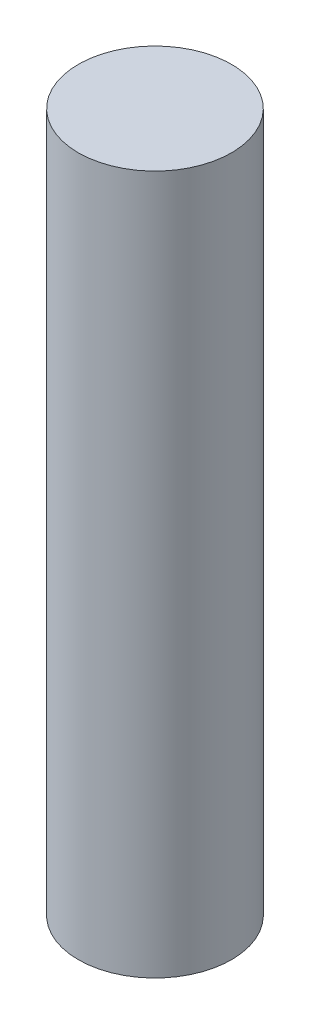
SolidWorks part; units mm, degrees
ref_plane "Front Plane" through (0, 0, 0) normal (0, 0, 1) x (1, 0, 0)
ref_plane "Top Plane" through (0, 0, 0) normal (0, 1, 0) x (1, 0, 0)
ref_plane "Right Plane" through (0, 0, 0) normal (1, 0, 0) x (0, 0, -1)
sketch "Sketch1" plane through (0, 0, 0) normal (0, 1, 0) x (1, 0, 0)
  circle A0 centre (0, 0) radius 50.8
  dimension "D1" = 101.6
extrude "Boss-Extrude1" add sketch "Sketch1" along normal blind 463.296
